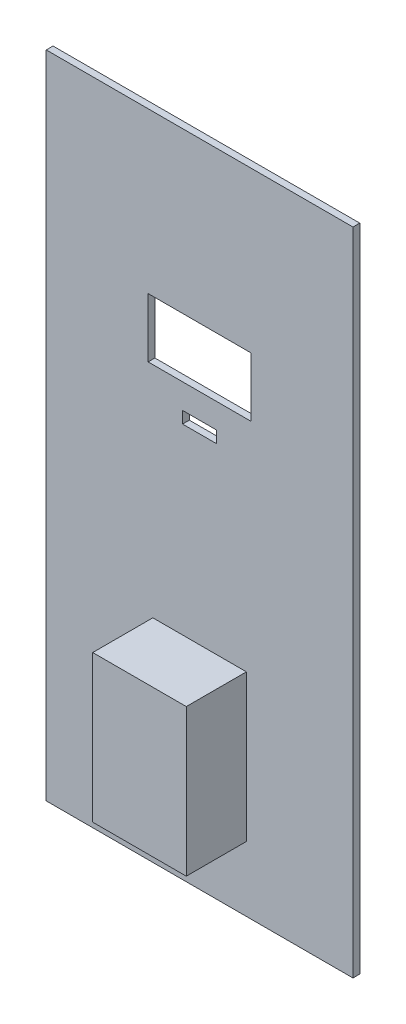
SolidWorks part; units mm, degrees
ref_plane "Front Plane" through (0, 0, 0) normal (0, 0, 1) x (1, 0, 0)
ref_plane "Top Plane" through (0, 0, 0) normal (0, 1, 0) x (1, 0, 0)
ref_plane "Right Plane" through (0, 0, 0) normal (1, 0, 0) x (0, 0, -1)
sketch "Sketch1" plane through (0, 0, 0) normal (0, 0, 1) x (1, 0, 0)
  line L1 (-287.5, 609.6) -> (287.5, 609.6)
  line L2 (-287.5, 609.6) -> (-287.5, -609.6)
  line L3 (-287.5, -609.6) -> (287.5, -609.6)
  line L4 (287.5, 609.6) -> (287.5, -609.6)
  line L5 (-287.5, 609.6) -> (287.5, -609.6) construction
  line L6 (-287.5, -609.6) -> (287.5, 609.6) construction
  point P0 (0, 0)
  dimension "D1" = 575
  dimension "D2" = 1219.2
extrude "Boss-Extrude1" add sketch "Sketch1" along normal blind 12.7
sketch "Sketch2" plane through (0, 0, 12.7) normal (0, 0, 1) x (1, 0, 0)
  line L0 (0, 0) -> (0, 254.1) construction
  line L1 (-96.5, 309.6) -> (96.5, 309.6)
  line L2 (-96.5, 309.6) -> (-96.5, 198.6)
  line L3 (-96.5, 198.6) -> (96.5, 198.6)
  line L4 (96.5, 309.6) -> (96.5, 198.6)
  line L5 (-96.5, 309.6) -> (96.5, 198.6) construction
  line L6 (-96.5, 198.6) -> (96.5, 309.6) construction
  line L7 (287.5, 609.6) -> (-287.5, 609.6) construction
  line L9 (32, 152.1285) -> (-32, 152.1285)
  line L10 (32, 152.1285) -> (32, 129.9385)
  line L11 (32, 129.9385) -> (-32, 129.9385)
  line L12 (-32, 152.1285) -> (-32, 129.9385)
  line L13 (32, 152.1285) -> (-32, 129.9385) construction
  line L14 (32, 129.9385) -> (-32, 152.1285) construction
  point P0 (0, 254.1)
  point P10 (0, 141.0335)
  dimension "D1" = 111
  dimension "D2" = 193
  dimension "D3" = 300
  dimension "D4" = 64
  dimension "D5" = 22.19
extrude "Cut-Extrude1" cut sketch "Sketch2" against normal blind 12.7
sketch "Sketch3" plane through (0, 0, 0) normal (0, 0, -1) x (-1, 0, 0)
  line L0 (0, 0) -> (0, -350.1632) construction
  line L2 (-75, -225.1632) -> (75, -225.1632)
  line L3 (-75, -225.1632) -> (-75, -475.1632)
  line L4 (-75, -475.1632) -> (75, -475.1632)
  line L5 (75, -225.1632) -> (75, -475.1632)
  line L6 (-75, -225.1632) -> (75, -475.1632) construction
  line L7 (-75, -475.1632) -> (75, -225.1632) construction
  dimension "D1" = 250
  dimension "D2" = 150
extrude "Cut-Extrude2" cut sketch "Sketch3" against normal blind 12.7
sketch "Sketch4" plane through (0, 0, 12.7) normal (0, 0, 1) x (1, 0, 0)
  line L0 (75, -475.1632) -> (-75, -475.1632) construction
  line L1 (75, -225.1632) -> (75, -475.1632) construction
  line L2 (-75, -475.1632) -> (-75, -225.1632) construction
  line L3 (-75, -225.1632) -> (75, -225.1632) construction
  line L4 (75, -475.1632) -> (-75, -475.1632)
  line L5 (75, -225.1632) -> (75, -475.1632)
  line L6 (-75, -475.1632) -> (-75, -225.1632)
  line L7 (-75, -225.1632) -> (75, -225.1632)
  line L8 (87.7, -487.8632) -> (-87.7, -487.8632)
  line L9 (-87.7, -487.8632) -> (-87.7, -212.4632)
  line L10 (-87.7, -212.4632) -> (87.7, -212.4632)
  line L11 (87.7, -212.4632) -> (87.7, -487.8632)
  dimension "D1" = 12.7
extrude "Boss-Extrude2" add sketch "Sketch4" along normal blind 100
sketch "Sketch5" plane through (0, 0, 112.7) normal (0, 0, 1) x (1, 0, 0)
  line L1 (87.7, -487.8632) -> (-87.7, -487.8632)
  line L2 (87.7, -487.8632) -> (87.7, -212.4632)
  line L3 (87.7, -212.4632) -> (-87.7, -212.4632)
  line L4 (-87.7, -487.8632) -> (-87.7, -212.4632)
extrude "Boss-Extrude3" add sketch "Sketch5" along normal blind 12.7
